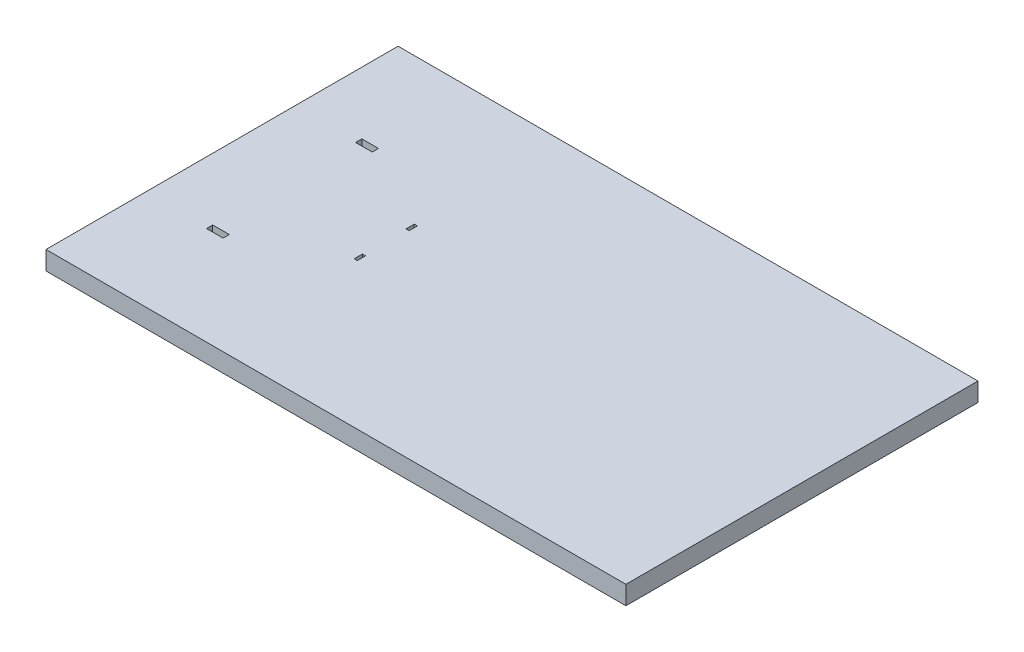
SolidWorks part; units mm, degrees
ref_plane "Front Plane" through (0, 0, 0) normal (0, 0, 1) x (1, 0, 0)
ref_plane "Top Plane" through (0, 0, 0) normal (0, 1, 0) x (1, 0, 0)
ref_plane "Right Plane" through (0, 0, 0) normal (1, 0, 0) x (0, 0, -1)
sketch "Sketch1" plane through (0, 0, 0) normal (0, 1, 0) x (1, 0, 0)
  line L1 (-14, -8.5) -> (14, -8.5)
  line L2 (-14, -8.5) -> (-14, 8.5)
  line L3 (-14, 8.5) -> (14, 8.5)
  line L4 (14, -8.5) -> (14, 8.5)
  line L5 (-14, -8.5) -> (14, 8.5) construction
  line L6 (-14, 8.5) -> (14, -8.5) construction
  line L7 (-11, -3.45) -> (-10.2, -3.45)
  line L8 (-11, -3.45) -> (-11, -3.75)
  line L9 (-11, -3.75) -> (-10.2, -3.75)
  line L10 (-10.2, -3.45) -> (-10.2, -3.75)
  line L11 (-11, 3.75) -> (-10.2, 3.75)
  line L12 (-11, 3.75) -> (-11, 3.45)
  line L13 (-11, 3.45) -> (-10.2, 3.45)
  line L14 (-10.2, 3.75) -> (-10.2, 3.45)
  line L15 (-6.17, -1.05) -> (-6.02, -1.05)
  line L16 (-6.17, -1.05) -> (-6.17, -1.45)
  line L17 (-6.17, -1.45) -> (-6.02, -1.45)
  line L18 (-6.02, -1.05) -> (-6.02, -1.45)
  line L19 (-6.17, 1.45) -> (-6.02, 1.45)
  line L20 (-6.17, 1.45) -> (-6.17, 1.05)
  line L21 (-6.17, 1.05) -> (-6.02, 1.05)
  line L22 (-6.02, 1.45) -> (-6.02, 1.05)
  point P0 (0, 0)
  dimension "D1" = 28
  dimension "D2" = 17
  dimension "D3" = 0.3
  dimension "D4" = 0.3
  dimension "D5" = 6.9
  dimension "D6" = 3.45
  dimension "D7" = 3
  dimension "D8" = 0.8
  dimension "D9" = 0.8
  dimension "D10" = 3
  dimension "D11" = 0.4
  dimension "D12" = 0.4
  dimension "D13" = 0.15
  dimension "D14" = 0.15
  dimension "D15" = 4.03
  dimension "D16" = 2.1
  dimension "D17" = 1.05
extrude "Boss-Extrude1" add sketch "Sketch1" along normal blind 0.9
